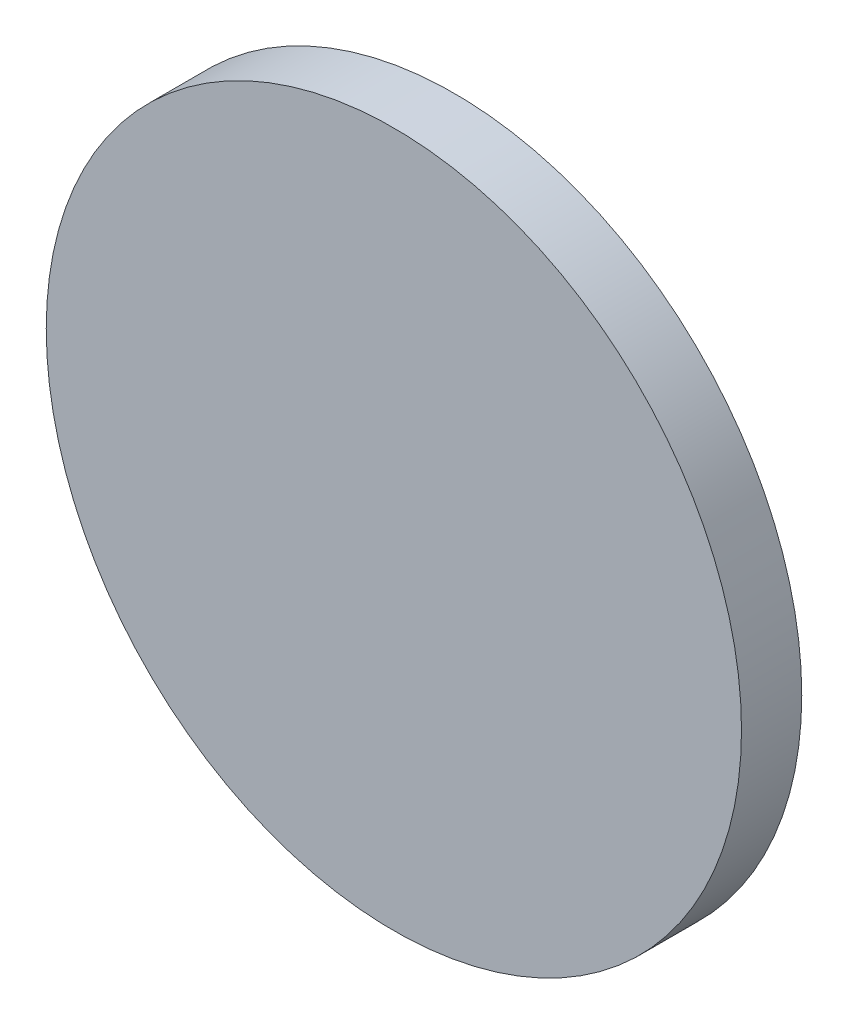
SolidWorks part; units mm, degrees
material "Glass"
ref_plane "Front Plane" through (0, 0, 0) normal (0, 0, 1) x (1, 0, 0)
ref_plane "Top Plane" through (0, 0, 0) normal (0, 1, 0) x (1, 0, 0)
ref_plane "Right Plane" through (0, 0, 0) normal (1, 0, 0) x (0, 0, -1)
sketch "Sketch1" plane through (0, 0, 0) normal (0, 0, 1) x (1, 0, 0)
  circle A0 centre (0, 0) radius 37.5
  dimension "D1" = 75
extrude "Boss-Extrude1" add sketch "Sketch1" along normal blind 6.5
